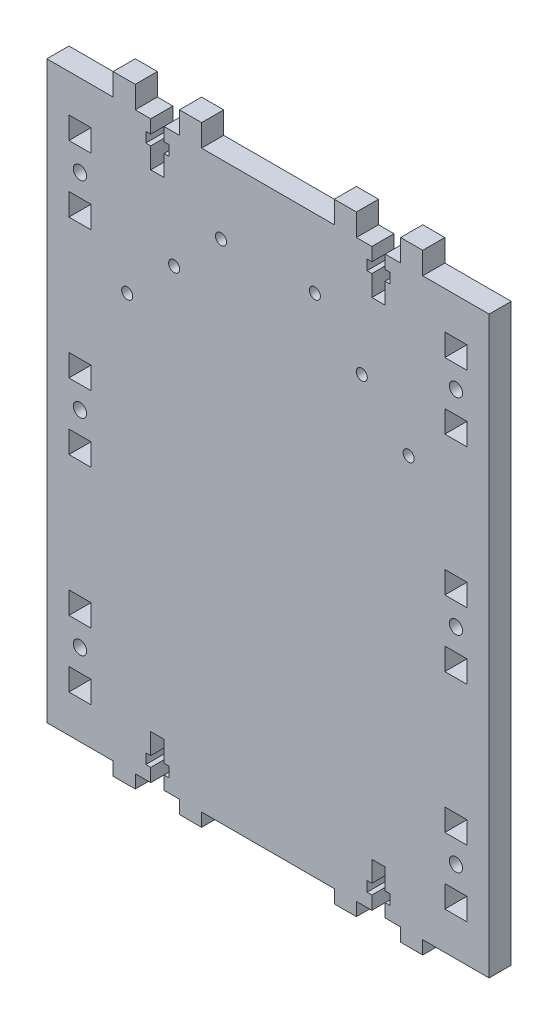
SolidWorks part; units mm, degrees
ref_plane "Front Plane" through (0, 0, 0) normal (0, 0, 1) x (1, 0, 0)
ref_plane "Top Plane" through (0, 0, 0) normal (0, 1, 0) x (1, 0, 0)
ref_plane "Right Plane" through (0, 0, 0) normal (1, 0, 0) x (0, 0, -1)
sketch "Sketch1" plane through (0, 0, 0) normal (0, 0, 1) x (1, 0, 0)
  line L0 (0, 0) -> (0, 58.8357) construction
  line L1 (-40, -65) -> (40, -65) construction
  line L2 (-40, -65) -> (-40, 65) construction
  line L3 (-40, 65) -> (40, 65) construction
  line L4 (40, -65) -> (40, 65) construction
  line L5 (-40, -65) -> (40, 65) construction
  line L6 (-40, 65) -> (40, -65) construction
  line L7 (-50, -65) -> (50, -65)
  line L8 (-50, -65) -> (-50, 65)
  line L9 (-50, 65) -> (50, 65)
  line L10 (50, -65) -> (50, 65)
  line L11 (-50, -65) -> (50, 65) construction
  line L12 (-50, 65) -> (50, -65) construction
  line L13 (0, 0) -> (33.0976, 0) construction
  line L15 (-35, 68) -> (-30, 68)
  line L16 (-35, 68) -> (-35, 70)
  line L17 (-35, 70) -> (-30, 70)
  line L18 (-30, 68) -> (-30, 70)
  line L19 (-20, 68) -> (-15, 68)
  line L20 (-20, 68) -> (-20, 70)
  line L21 (-20, 70) -> (-15, 70)
  line L22 (-15, 68) -> (-15, 70)
  line L23 (15, 68) -> (20, 68)
  line L24 (15, 68) -> (15, 70)
  line L25 (15, 70) -> (20, 70)
  line L26 (20, 68) -> (20, 70)
  line L27 (30, 68) -> (35, 68)
  line L28 (30, 68) -> (30, 70)
  line L29 (30, 70) -> (35, 70)
  line L30 (35, 68) -> (35, 70)
  line L31 (-40, -67.8318) -> (-40, 2.1682) construction
  line L33 (0, -67.8318) -> (-40, -67.8318) construction
  circle A0 centre (-31.8198, 28.1768) radius 1.25
  circle A1 centre (-21.2132, 38.7834) radius 1.25
  circle A2 centre (-10.6066, 49.39) radius 1.25
  circle A3 centre (10.6066, 49.39) radius 1.25
  circle A4 centre (21.2132, 38.7834) radius 1.25
  circle A5 centre (31.8198, 28.1768) radius 1.25
  point P1 (0, 0)
  point P6 (0, 0)
  point P11 (25, 58.3911)
  point P31 (0, 58.8357)
  point P35 (0, 55.3459)
  point P36 (0, 48.0466)
  point P38 (0, 32.8645)
  point P39 (0, 33.8891)
  point P59 (107.816, 43.3959)
  point P60 (18.211, 57.35)
  line B0 (42.5, 41.5) -> (42.5, 51.5) construction
  line B1 (40, 41.5) -> (40, 36.5)
  line B2 (40, 41.5) -> (45, 41.5)
  line B3 (45, 41.5) -> (45, 36.5)
  line B4 (40, 36.5) -> (45, 36.5)
  line B5 (40, 51.5) -> (40, 56.5)
  line B6 (40, 51.5) -> (45, 51.5)
  line B7 (45, 51.5) -> (45, 56.5)
  line B8 (40, 56.5) -> (45, 56.5)
  line B9 (42.5, 46.5) -> (35.5276, 46.5) construction
  circle B10 centre (42.5, 46.5) radius 1.5
  line B11 (42.5, -5) -> (42.5, 5) construction
  line B12 (40, -5) -> (40, -10)
  line B13 (40, -5) -> (45, -5)
  line B14 (45, -5) -> (45, -10)
  line B15 (40, -10) -> (45, -10)
  line B16 (40, 5) -> (40, 10)
  line B17 (40, 5) -> (45, 5)
  line B18 (45, 5) -> (45, 10)
  line B19 (40, 10) -> (45, 10)
  line B20 (42.5, 0) -> (35.5276, 0) construction
  circle B21 centre (42.5, 0) radius 1.5
  line B22 (42.5, -41.5) -> (42.5, -51.5) construction
  line B23 (40, -41.5) -> (40, -36.5)
  line B24 (40, -41.5) -> (45, -41.5)
  line B25 (45, -41.5) -> (45, -36.5)
  line B26 (40, -36.5) -> (45, -36.5)
  line B27 (40, -51.5) -> (40, -56.5)
  line B28 (40, -51.5) -> (45, -51.5)
  line B29 (45, -51.5) -> (45, -56.5)
  line B30 (40, -56.5) -> (45, -56.5)
  line B31 (42.5, -46.5) -> (35.5276, -46.5) construction
  circle B32 centre (42.5, -46.5) radius 1.5
  line B33 (-42.5, -5) -> (-42.5, 5) construction
  line B34 (-40, -5) -> (-40, -10)
  line B35 (-40, -5) -> (-45, -5)
  line B36 (-45, -5) -> (-45, -10)
  line B37 (-40, -10) -> (-45, -10)
  line B38 (-40, 5) -> (-40, 10)
  line B39 (-40, 5) -> (-45, 5)
  line B40 (-45, 5) -> (-45, 10)
  line B41 (-40, 10) -> (-45, 10)
  line B42 (-42.5, 0) -> (-35.5276, 0) construction
  circle B43 centre (-42.5, 0) radius 1.5
  line B44 (-42.5, 41.5) -> (-42.5, 51.5) construction
  line B45 (-40, 41.5) -> (-40, 36.5)
  line B46 (-40, 41.5) -> (-45, 41.5)
  line B47 (-45, 41.5) -> (-45, 36.5)
  line B48 (-40, 36.5) -> (-45, 36.5)
  line B49 (-40, 51.5) -> (-40, 56.5)
  line B50 (-40, 51.5) -> (-45, 51.5)
  line B51 (-45, 51.5) -> (-45, 56.5)
  line B52 (-40, 56.5) -> (-45, 56.5)
  line B53 (-42.5, 46.5) -> (-35.5276, 46.5) construction
  circle B54 centre (-42.5, 46.5) radius 1.5
  line B55 (-42.5, -41.5) -> (-42.5, -51.5) construction
  line B56 (-40, -41.5) -> (-40, -36.5)
  line B57 (-40, -41.5) -> (-45, -41.5)
  line B58 (-45, -41.5) -> (-45, -36.5)
  line B59 (-40, -36.5) -> (-45, -36.5)
  line B60 (-40, -51.5) -> (-40, -56.5)
  line B61 (-40, -51.5) -> (-45, -51.5)
  line B62 (-45, -51.5) -> (-45, -56.5)
  line B63 (-40, -56.5) -> (-45, -56.5)
  line B64 (-42.5, -46.5) -> (-35.5276, -46.5) construction
  circle B65 centre (-42.5, -46.5) radius 1.5
  line B66 (-27.6, -62) -> (-27.6, -59.7)
  line B67 (-23.5, -59.7) -> (-23.5, -55)
  line B68 (-26.5, -55) -> (-26.5, -59.7)
  line B69 (-27.6, -59.7) -> (-26.5, -59.7)
  line B70 (-25, -65) -> (-25, -51.7823) construction
  line B71 (-26.5, -65) -> (-30, -65)
  line B72 (-30, -68) -> (-35, -68)
  line B73 (-35, -68) -> (-35, -65)
  line B74 (-30, -68) -> (-30, -65)
  line B75 (-23.5, -65) -> (-20, -65)
  line B76 (-20, -65) -> (-20, -68)
  line B77 (-20, -68) -> (-15, -68)
  line B78 (-15, -68) -> (-15, -65)
  line B79 (-26.5, -65) -> (-23.5, -65) construction
  line B80 (-23.5, -65) -> (-23.5, -62)
  line B81 (-23.5, -59.7) -> (-22.4, -59.7)
  line B82 (-22.4, -62) -> (-23.5, -62)
  line B83 (-23.5, -55) -> (-26.5, -55)
  line B84 (-26.5, -62) -> (-27.6, -62)
  line B85 (-22.4, -59.7) -> (-22.4, -62)
  line B86 (-26.5, -62) -> (-26.5, -65)
  line B87 (-25, -55) -> (-25, -65) construction
  line B88 (27.6, -62) -> (27.6, -59.7)
  line B89 (23.5, -59.7) -> (23.5, -55)
  line B90 (26.5, -55) -> (26.5, -59.7)
  line B91 (27.6, -59.7) -> (26.5, -59.7)
  line B92 (25, -65) -> (25, -51.7823) construction
  line B93 (26.5, -65) -> (30, -65)
  line B94 (30, -68) -> (35, -68)
  line B95 (35, -68) -> (35, -65)
  line B96 (30, -68) -> (30, -65)
  line B97 (23.5, -65) -> (20, -65)
  line B98 (20, -65) -> (20, -68)
  line B99 (20, -68) -> (15, -68)
  line B100 (15, -68) -> (15, -65)
  line B101 (26.5, -65) -> (23.5, -65) construction
  line B102 (23.5, -65) -> (23.5, -62)
  line B103 (23.5, -59.7) -> (22.4, -59.7)
  line B104 (22.4, -62) -> (23.5, -62)
  line B105 (23.5, -55) -> (26.5, -55)
  line B106 (26.5, -62) -> (27.6, -62)
  line B107 (22.4, -59.7) -> (22.4, -62)
  line B108 (26.5, -62) -> (26.5, -65)
  line B109 (25, -55) -> (25, -65) construction
  line B110 (-22.4, 62) -> (-22.4, 59.7)
  line B111 (-26.5, 59.7) -> (-26.5, 55)
  line B112 (-23.5, 55) -> (-23.5, 59.7)
  line B113 (-22.4, 59.7) -> (-23.5, 59.7)
  line B114 (-25, 65) -> (-25, 51.7823) construction
  line B115 (-23.5, 65) -> (-20, 65)
  line B116 (-20, 68) -> (-15, 68)
  line B117 (-15, 68) -> (-15, 65)
  line B118 (-20, 68) -> (-20, 65)
  line B119 (-26.5, 65) -> (-30, 65)
  line B120 (-30, 65) -> (-30, 68)
  line B121 (-30, 68) -> (-35, 68)
  line B122 (-35, 68) -> (-35, 65)
  line B123 (-23.5, 65) -> (-26.5, 65) construction
  line B124 (-26.5, 65) -> (-26.5, 62)
  line B125 (-26.5, 59.7) -> (-27.6, 59.7)
  line B126 (-27.6, 62) -> (-26.5, 62)
  line B127 (-26.5, 55) -> (-23.5, 55)
  line B128 (-23.5, 62) -> (-22.4, 62)
  line B129 (-27.6, 59.7) -> (-27.6, 62)
  line B130 (-23.5, 62) -> (-23.5, 65)
  line B131 (-25, 55) -> (-25, 65) construction
  line B132 (27.6, 62) -> (27.6, 59.7)
  line B133 (23.5, 59.7) -> (23.5, 55)
  line B134 (26.5, 55) -> (26.5, 59.7)
  line B135 (27.6, 59.7) -> (26.5, 59.7)
  line B136 (25, 65) -> (25, 51.7823) construction
  line B137 (26.5, 65) -> (30, 65)
  line B138 (30, 68) -> (35, 68)
  line B139 (35, 68) -> (35, 65)
  line B140 (30, 68) -> (30, 65)
  line B141 (23.5, 65) -> (20, 65)
  line B142 (20, 65) -> (20, 68)
  line B143 (20, 68) -> (15, 68)
  line B144 (15, 68) -> (15, 65)
  line B145 (26.5, 65) -> (23.5, 65) construction
  line B146 (23.5, 65) -> (23.5, 62)
  line B147 (23.5, 59.7) -> (22.4, 59.7)
  line B148 (22.4, 62) -> (23.5, 62)
  line B149 (23.5, 55) -> (26.5, 55)
  line B150 (26.5, 62) -> (27.6, 62)
  line B151 (22.4, 59.7) -> (22.4, 62)
  line B152 (26.5, 62) -> (26.5, 65)
  line B153 (25, 55) -> (25, 65) construction
  dimension "D17" = 2.5
  dimension "D11" = 31.8198
  dimension "D12" = 15.61
  dimension "D1" = 130
  dimension "D2" = 80
  dimension "D3" = 18.5
  dimension "D4" = 25
  dimension "D5" = 100
  dimension "D6" = 2
  dimension "D7" = 5
  dimension "D8" = 70
  dimension "D9" = 10.6066
  dimension "D10" = 21.2132
  dimension "D15" = 15
  dimension "D16" = 15
sketch_block_instance "Trou M3 plots 5mm-1"
sketch_block "Trou M3 plots 5mm" parameters "D2"=3, "D1"=5, "D3"=5, "D4"=10
sketch_block_instance "Trou M3 plots 5mm-2"
sketch_block_instance "Trou M3 plots 5mm-5"
sketch_block_instance "Trou M3 plots 5mm-6"
sketch_block_instance "Trou M3 plots 5mm-7"
sketch_block_instance "Trou M3 plots 5mm-8"
sketch_block_instance "Insert M3 plots ep 3mm-1"
sketch_block "Insert M3 plots ep 3mm" parameters "D1"=10, "D2"=5, "D3"=3
sketch_block_instance "Decoupe Insert M3-4"
sketch_block "Decoupe Insert M3" parameters "D1"=5.2, "D2"=3, "D3"=2.3, "D4"=3, "D5"=10
sketch_block_instance "Insert M3 plots ep 3mm-5"
sketch_block_instance "Insert M3 plots ep 3mm-12"
sketch_block_instance "Insert M3 plots ep 3mm-14"
extrude "Boss-Extrude1" add sketch "Sketch1" along normal blind 5 contours B152 B150 B132 B135 B134 B149 B133 B147 B151 B148 B146 L9 B130 B128 B110 B113 B112 B127 B111 B125 B129 B126 B124 L8 L7 B86 B84 B66 B69 B68 B83 B67 B81 B85 B82 B80 B102 | L15 B122 L9 B120 | L19 B118 L9 B117 | L19 L22 L21 L20 | L15 L18 L17 L16 | L23 B144 L9 B142 | L23 L26 L25 L24 | L27 L30 L29 L28 | L27 B140 L9 B139 | B72 B74 L7 B73 | B77 B78 L7 B76 | B100 B99 B98 L7 | B96 B94 B95 L7
